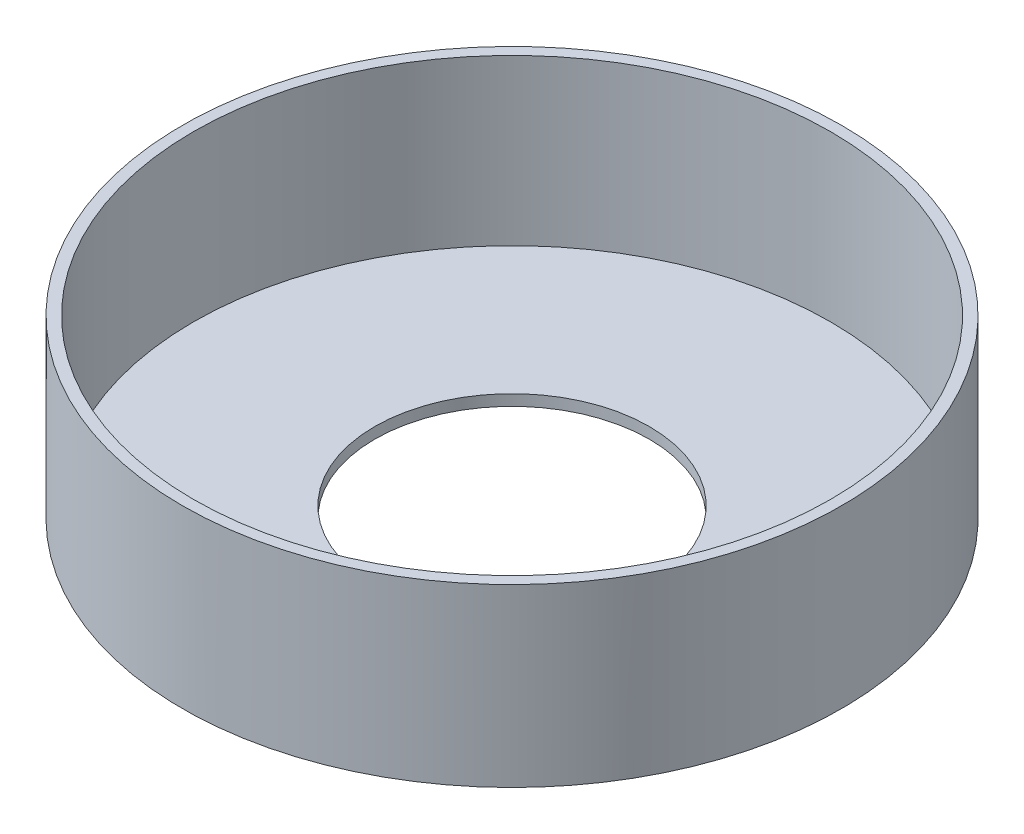
SolidWorks part; units mm, degrees
ref_plane "Front Plane" through (0, 0, 0) normal (0, 0, 1) x (1, 0, 0)
ref_plane "Top Plane" through (0, 0, 0) normal (0, 1, 0) x (1, 0, 0)
ref_plane "Right Plane" through (0, 0, 0) normal (1, 0, 0) x (0, 0, -1)
sketch "Sketch1" plane through (0, 0, 0) normal (0, 1, 0) x (1, 0, 0)
  circle A0 centre (0, 0) radius 29
  circle A1 centre (0, 0) radius 30
  dimension "D1" = 1
  dimension "D2" = 58
extrude "Boss-Extrude1" add sketch "Sketch1" along normal blind 15
sketch "Sketch2" plane through (0, 0, 0) normal (0, -1, 0) x (1, 0, 0)
  circle A0 centre (0, 0) radius 30
  circle A1 centre (0, 0) radius 12.5
  dimension "D1" = 25
extrude "Boss-Extrude2" add sketch "Sketch2" along normal blind 1
